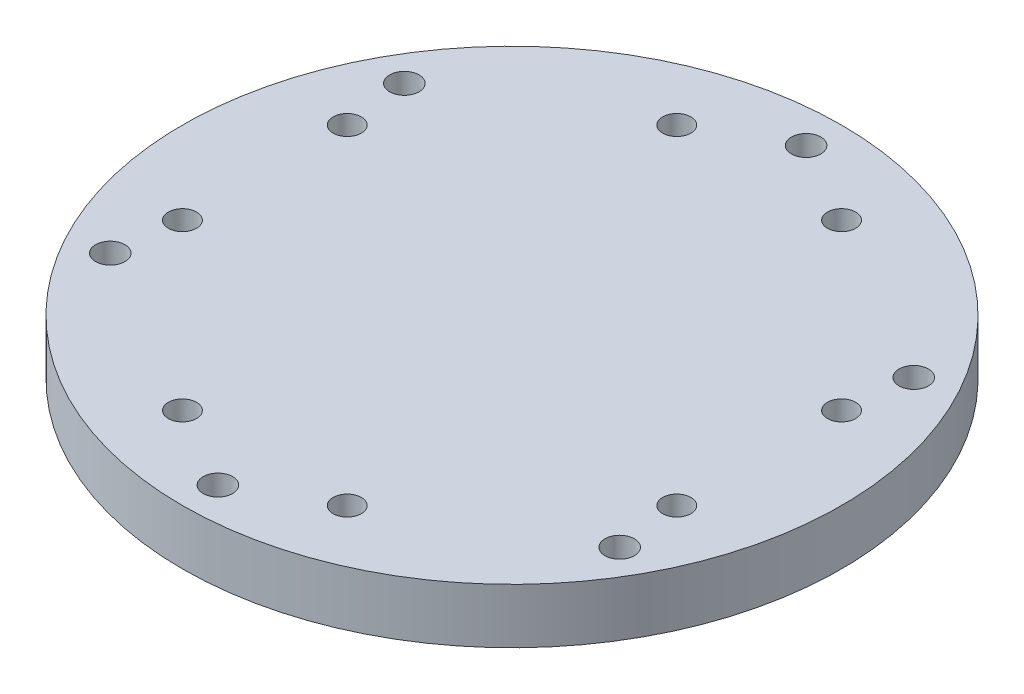
SolidWorks part; units mm, degrees
other "Markup1"
sketch "Sketch10" plane through (-85, 12.7, 85) normal (0, 1, 0) x (-1, 0, 0)
material "ASTM A36 Steel"
ref_plane "Front Plane" through (0, 0, 0) normal (0, 0, 1) x (1, 0, 0)
ref_plane "Top Plane" through (0, 0, 0) normal (0, 1, 0) x (1, 0, 0)
ref_plane "Right Plane" through (0, 0, 0) normal (1, 0, 0) x (0, 0, -1)
sketch "Sketch1" plane through (0, 0, 0) normal (0, 1, 0) x (1, 0, 0)
  circle A0 centre (0, 0) radius 76.2
  dimension "D3" = 152.4
extrude "Boss-Extrude1" add sketch "Sketch1" along normal blind 12.7
hole_wizard "M8x1.25 Tapped Hole1" positions "Sketch3" profile "Sketch5" tap size "M8x1.25" standard "ANSI Metric" end condition through all
sketch "Sketch3" plane through (0, 12.7, 0) normal (0, 1, 0) x (1, 0, 0)
  point P0 (0, 68)
  point P5 (0, 68)
  dimension "D1" = 68
cosmetic thread "Hole Thread1"
cosmetic thread "Hole Thread15"
sketch "Sketch5" plane through (0, 12.7, -68) normal (1, 0, 0) x (0, 0, 1)
  line L0 (0, 0) -> (0, 12.7)
  line L1 (0, 12.7) -> (3.4, 12.7)
  line L2 (3.4, 12.7) -> (3.4, 0)
  line L5 (3.4, 0) -> (0, 0)
  line L11 (0, -6.35) -> (0, 107.95) construction
  dimension "Thru Tap Drill Dia." = 6.8
  dimension "Thru Tap Drill Depth" = 12.7
sketch "Sketch13" plane through (0, 0, 0) normal (0, 0, 1) x (1, 0, 0)
  line L0 (0, 0) -> (0, 28.9496) construction
pattern_circular "CirPattern3" count 6 every 60 about axis through (0, 0, 0) along (0, 1, 0) of "M8x1.25 Tapped Hole1"
cosmetic thread "Hole Thread21" parameters "D2"=8
cosmetic thread "Hole Thread22" parameters "D2"=8
cosmetic thread "Hole Thread23" parameters "D2"=8
cosmetic thread "Hole Thread24" parameters "D2"=8
cosmetic thread "Hole Thread25" parameters "D2"=8
cosmetic thread "Hole Thread26" parameters "D2"=8
cosmetic thread "Hole Thread27" parameters "D2"=8
cosmetic thread "Hole Thread28" parameters "D2"=8
cosmetic thread "Hole Thread29" parameters "D2"=8
cosmetic thread "Hole Thread30" parameters "D2"=8
hole_wizard "5/16-18 Tapped Hole1" positions "Sketch8" profile "Sketch9" tap size "5/16-18" standard "ANSI Inch" end condition through all
sketch "Sketch8" plane through (0, 0, 0) normal (0, -1, 0) x (-1, 0, 0)
  point P0 (-19.05, 57.15)
  point P3 (19.05, 57.15)
  dimension "D1" = 57.15
  dimension "D2" = 19.05
  dimension "D3" = 57.15
  dimension "D4" = 19.05
sketch "Sketch9" plane through (19.05, 0, -57.15) normal (1, 0, 0) x (0, 0, -1)
  line L0 (0, 0) -> (0, 12.7)
  line L1 (0, 12.7) -> (3.2639, 12.7)
  line L2 (3.2639, 12.7) -> (3.2639, 0)
  line L5 (3.2639, 0) -> (0, 0)
  line L11 (0, -6.35) -> (0, 107.95) construction
  dimension "Thru Tap Drill Dia." = 6.5278
  dimension "Thru Tap Drill Depth" = 12.7
cosmetic thread "Hole Thread7" parameters "D2"=7.9375
cosmetic thread "Hole Thread8" parameters "D2"=7.9375
pattern_circular "CirPattern2" count 4 over 360 about axis through (0, 0, 0) along (0, 1, 0) of "5/16-18 Tapped Hole1"
cosmetic thread "Hole Thread9"
cosmetic thread "Hole Thread10"
cosmetic thread "Hole Thread11"
cosmetic thread "Hole Thread12"
cosmetic thread "Hole Thread13"
cosmetic thread "Hole Thread14"
equation "\"D1@Sketch3\"=(136/2)"
equation "\"D3@Sketch8\"=\"D1@Sketch8\""
equation "\"D4@Sketch8\"=\"D2@Sketch8\""
